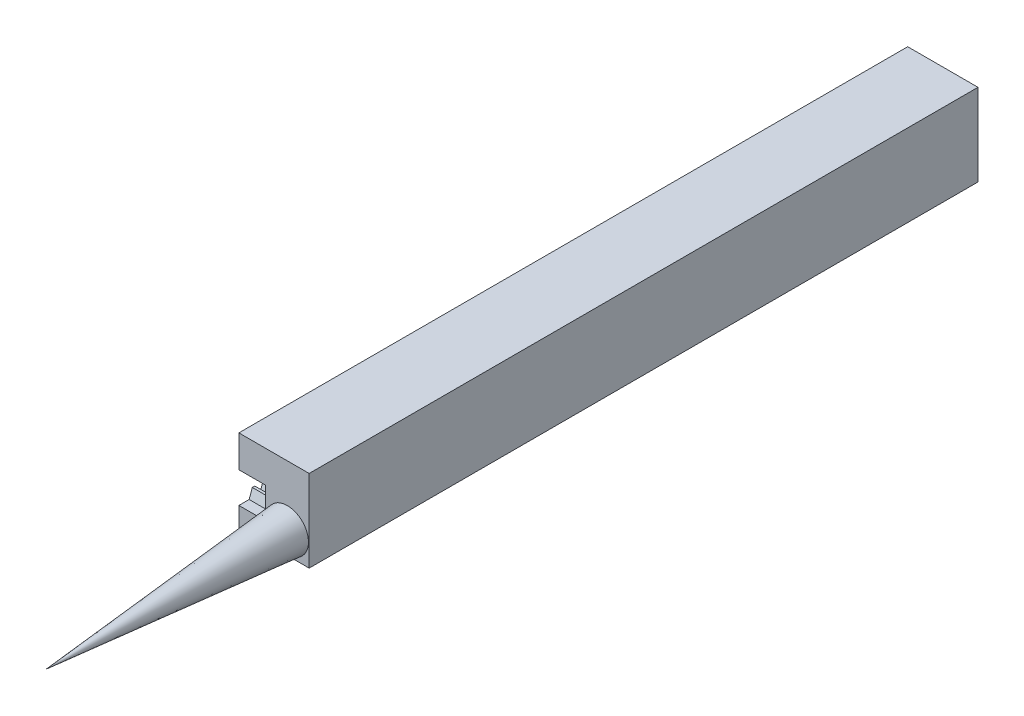
SolidWorks part; units mm, degrees
ref_plane "Ebene vorne" through (0, 0, 0) normal (0, 0, 1) x (1, 0, 0)
ref_plane "Ebene oben" through (0, 0, 0) normal (0, 1, 0) x (1, 0, 0)
ref_plane "Ebene rechts" through (0, 0, 0) normal (1, 0, 0) x (0, 0, -1)
sketch "Skizze1" plane through (0, 0, 0) normal (0, 0, 1) x (1, 0, 0)
  line L1 (-33, -38.5) -> (33, -38.5)
  line L2 (-33, -38.5) -> (-33, 38.5)
  line L3 (-33, 38.5) -> (33, 38.5)
  line L4 (33, -38.5) -> (33, 38.5)
  line L5 (-33, -38.5) -> (33, 38.5) construction
  line L6 (-33, 38.5) -> (33, -38.5) construction
  point P0 (0, 0)
  dimension "D1" = 77
  dimension "D2" = 66
extrude "Aufsatz-Linear austragen1" add sketch "Skizze1" along normal blind 628
sketch "Skizze2" plane through (0, 0, 0) normal (0, 0, -1) x (-1, 0, 0)
  line L0 (33, -20.5) -> (33, 8.5)
  line L1 (33, -20.5) -> (8, -20.5)
  line L2 (33, 8.5) -> (8, 8.5)
  line L3 (8, -20.5) -> (8, 8.5)
  line L4 (33, 38.5) -> (33, -38.5) construction
  line L5 (33, -38.5) -> (-33, -38.5) construction
  dimension "D1" = 18
  dimension "D2" = 25
  dimension "D3" = 29
extrude "Schnitt-Linear austragen1" cut sketch "Skizze2" against normal up to surface (628 mm away) up to face at (0, 0, 628)
sketch "Skizze3" plane through (-8, 0, 0) normal (-1, 0, 0) x (0, 0, 1)
  line L0 (18.367, -20.5) -> (10, -20.5)
  line L1 (0, -20.5) -> (3.0059, -12.2151)
  line L2 (3.0059, -12.2151) -> (5.361, -12.2151)
  line L3 (5.361, -12.2151) -> (8.367, -20.5)
  line L4 (628, -20.5) -> (0, -20.5) construction
  line L5 (8.367, -20.5) -> (0, -20.5)
  line L6 (10, -20.5) -> (13.0059, -12.2151)
  line L7 (13.0059, -12.2151) -> (15.361, -12.2151)
  line L8 (15.361, -12.2151) -> (18.367, -20.5)
  line L9 (28.367, -20.5) -> (20, -20.5)
  line L10 (20, -20.5) -> (23.0059, -12.2151)
  line L11 (23.0059, -12.2151) -> (25.361, -12.2151)
  line L12 (25.361, -12.2151) -> (28.367, -20.5)
  line L13 (38.367, -20.5) -> (30, -20.5)
  line L14 (30, -20.5) -> (33.0059, -12.2151)
  line L15 (33.0059, -12.2151) -> (35.361, -12.2151)
  line L16 (35.361, -12.2151) -> (38.367, -20.5)
  line L17 (48.367, -20.5) -> (40, -20.5)
  line L18 (40, -20.5) -> (43.0059, -12.2151)
  line L19 (43.0059, -12.2151) -> (45.361, -12.2151)
  line L20 (45.361, -12.2151) -> (48.367, -20.5)
  line L21 (58.367, -20.5) -> (50, -20.5)
  line L22 (50, -20.5) -> (53.0059, -12.2151)
  line L23 (53.0059, -12.2151) -> (55.361, -12.2151)
  line L24 (55.361, -12.2151) -> (58.367, -20.5)
  line L25 (68.367, -20.5) -> (60, -20.5)
  line L26 (60, -20.5) -> (63.0059, -12.2151)
  line L27 (63.0059, -12.2151) -> (65.361, -12.2151)
  line L28 (65.361, -12.2151) -> (68.367, -20.5)
  line L29 (78.367, -20.5) -> (70, -20.5)
  line L30 (70, -20.5) -> (73.0059, -12.2151)
  line L31 (73.0059, -12.2151) -> (75.361, -12.2151)
  line L32 (75.361, -12.2151) -> (78.367, -20.5)
  line L33 (88.367, -20.5) -> (80, -20.5)
  line L34 (80, -20.5) -> (83.0059, -12.2151)
  line L35 (83.0059, -12.2151) -> (85.361, -12.2151)
  line L36 (85.361, -12.2151) -> (88.367, -20.5)
  line L37 (98.367, -20.5) -> (90, -20.5)
  line L38 (90, -20.5) -> (93.0059, -12.2151)
  line L39 (93.0059, -12.2151) -> (95.361, -12.2151)
  line L40 (95.361, -12.2151) -> (98.367, -20.5)
  line L41 (108.367, -20.5) -> (100, -20.5)
  line L42 (100, -20.5) -> (103.0059, -12.2151)
  line L43 (103.0059, -12.2151) -> (105.361, -12.2151)
  line L44 (105.361, -12.2151) -> (108.367, -20.5)
  line L45 (118.367, -20.5) -> (110, -20.5)
  line L46 (110, -20.5) -> (113.0059, -12.2151)
  line L47 (113.0059, -12.2151) -> (115.361, -12.2151)
  line L48 (115.361, -12.2151) -> (118.367, -20.5)
  line L49 (128.367, -20.5) -> (120, -20.5)
  line L50 (120, -20.5) -> (123.0059, -12.2151)
  line L51 (123.0059, -12.2151) -> (125.361, -12.2151)
  line L52 (125.361, -12.2151) -> (128.367, -20.5)
  line L53 (138.367, -20.5) -> (130, -20.5)
  line L54 (130, -20.5) -> (133.0059, -12.2151)
  line L55 (133.0059, -12.2151) -> (135.361, -12.2151)
  line L56 (135.361, -12.2151) -> (138.367, -20.5)
  line L57 (148.367, -20.5) -> (140, -20.5)
  line L58 (140, -20.5) -> (143.0059, -12.2151)
  line L59 (143.0059, -12.2151) -> (145.361, -12.2151)
  line L60 (145.361, -12.2151) -> (148.367, -20.5)
  line L61 (158.367, -20.5) -> (150, -20.5)
  line L62 (150, -20.5) -> (153.0059, -12.2151)
  line L63 (153.0059, -12.2151) -> (155.361, -12.2151)
  line L64 (155.361, -12.2151) -> (158.367, -20.5)
  line L65 (168.367, -20.5) -> (160, -20.5)
  line L66 (160, -20.5) -> (163.0059, -12.2151)
  line L67 (163.0059, -12.2151) -> (165.361, -12.2151)
  line L68 (165.361, -12.2151) -> (168.367, -20.5)
  line L69 (178.367, -20.5) -> (170, -20.5)
  line L70 (170, -20.5) -> (173.0059, -12.2151)
  line L71 (173.0059, -12.2151) -> (175.361, -12.2151)
  line L72 (175.361, -12.2151) -> (178.367, -20.5)
  line L73 (188.367, -20.5) -> (180, -20.5)
  line L74 (180, -20.5) -> (183.0059, -12.2151)
  line L75 (183.0059, -12.2151) -> (185.361, -12.2151)
  line L76 (185.361, -12.2151) -> (188.367, -20.5)
  line L77 (198.367, -20.5) -> (190, -20.5)
  line L78 (190, -20.5) -> (193.0059, -12.2151)
  line L79 (193.0059, -12.2151) -> (195.361, -12.2151)
  line L80 (195.361, -12.2151) -> (198.367, -20.5)
  line L81 (208.367, -20.5) -> (200, -20.5)
  line L82 (200, -20.5) -> (203.0059, -12.2151)
  line L83 (203.0059, -12.2151) -> (205.361, -12.2151)
  line L84 (205.361, -12.2151) -> (208.367, -20.5)
  line L85 (218.367, -20.5) -> (210, -20.5)
  line L86 (210, -20.5) -> (213.0059, -12.2151)
  line L87 (213.0059, -12.2151) -> (215.361, -12.2151)
  line L88 (215.361, -12.2151) -> (218.367, -20.5)
  line L89 (228.367, -20.5) -> (220, -20.5)
  line L90 (220, -20.5) -> (223.0059, -12.2151)
  line L91 (223.0059, -12.2151) -> (225.361, -12.2151)
  line L92 (225.361, -12.2151) -> (228.367, -20.5)
  line L93 (238.367, -20.5) -> (230, -20.5)
  line L94 (230, -20.5) -> (233.0059, -12.2151)
  line L95 (233.0059, -12.2151) -> (235.361, -12.2151)
  line L96 (235.361, -12.2151) -> (238.367, -20.5)
  line L97 (248.367, -20.5) -> (240, -20.5)
  line L98 (240, -20.5) -> (243.0059, -12.2151)
  line L99 (243.0059, -12.2151) -> (245.361, -12.2151)
  line L100 (245.361, -12.2151) -> (248.367, -20.5)
  line L101 (258.367, -20.5) -> (250, -20.5)
  line L102 (250, -20.5) -> (253.0059, -12.2151)
  line L103 (253.0059, -12.2151) -> (255.361, -12.2151)
  line L104 (255.361, -12.2151) -> (258.367, -20.5)
  line L105 (268.367, -20.5) -> (260, -20.5)
  line L106 (260, -20.5) -> (263.0059, -12.2151)
  line L107 (263.0059, -12.2151) -> (265.361, -12.2151)
  line L108 (265.361, -12.2151) -> (268.367, -20.5)
  line L109 (278.367, -20.5) -> (270, -20.5)
  line L110 (270, -20.5) -> (273.0059, -12.2151)
  line L111 (273.0059, -12.2151) -> (275.361, -12.2151)
  line L112 (275.361, -12.2151) -> (278.367, -20.5)
  line L113 (288.367, -20.5) -> (280, -20.5)
  line L114 (280, -20.5) -> (283.0059, -12.2151)
  line L115 (283.0059, -12.2151) -> (285.361, -12.2151)
  line L116 (285.361, -12.2151) -> (288.367, -20.5)
  line L117 (298.367, -20.5) -> (290, -20.5)
  line L118 (290, -20.5) -> (293.0059, -12.2151)
  line L119 (293.0059, -12.2151) -> (295.361, -12.2151)
  line L120 (295.361, -12.2151) -> (298.367, -20.5)
  line L121 (308.367, -20.5) -> (300, -20.5)
  line L122 (300, -20.5) -> (303.0059, -12.2151)
  line L123 (303.0059, -12.2151) -> (305.361, -12.2151)
  line L124 (305.361, -12.2151) -> (308.367, -20.5)
  line L125 (318.367, -20.5) -> (310, -20.5)
  line L126 (310, -20.5) -> (313.0059, -12.2151)
  line L127 (313.0059, -12.2151) -> (315.361, -12.2151)
  line L128 (315.361, -12.2151) -> (318.367, -20.5)
  line L129 (328.367, -20.5) -> (320, -20.5)
  line L130 (320, -20.5) -> (323.0059, -12.2151)
  line L131 (323.0059, -12.2151) -> (325.361, -12.2151)
  line L132 (325.361, -12.2151) -> (328.367, -20.5)
  line L133 (338.367, -20.5) -> (330, -20.5)
  line L134 (330, -20.5) -> (333.0059, -12.2151)
  line L135 (333.0059, -12.2151) -> (335.361, -12.2151)
  line L136 (335.361, -12.2151) -> (338.367, -20.5)
  line L137 (348.367, -20.5) -> (340, -20.5)
  line L138 (340, -20.5) -> (343.0059, -12.2151)
  line L139 (343.0059, -12.2151) -> (345.361, -12.2151)
  line L140 (345.361, -12.2151) -> (348.367, -20.5)
  line L141 (358.367, -20.5) -> (350, -20.5)
  line L142 (350, -20.5) -> (353.0059, -12.2151)
  line L143 (353.0059, -12.2151) -> (355.361, -12.2151)
  line L144 (355.361, -12.2151) -> (358.367, -20.5)
  line L145 (368.367, -20.5) -> (360, -20.5)
  line L146 (360, -20.5) -> (363.0059, -12.2151)
  line L147 (363.0059, -12.2151) -> (365.361, -12.2151)
  line L148 (365.361, -12.2151) -> (368.367, -20.5)
  line L149 (378.367, -20.5) -> (370, -20.5)
  line L150 (370, -20.5) -> (373.0059, -12.2151)
  line L151 (373.0059, -12.2151) -> (375.361, -12.2151)
  line L152 (375.361, -12.2151) -> (378.367, -20.5)
  line L153 (388.367, -20.5) -> (380, -20.5)
  line L154 (380, -20.5) -> (383.0059, -12.2151)
  line L155 (383.0059, -12.2151) -> (385.361, -12.2151)
  line L156 (385.361, -12.2151) -> (388.367, -20.5)
  line L157 (398.367, -20.5) -> (390, -20.5)
  line L158 (390, -20.5) -> (393.0059, -12.2151)
  line L159 (393.0059, -12.2151) -> (395.361, -12.2151)
  line L160 (395.361, -12.2151) -> (398.367, -20.5)
  line L161 (408.367, -20.5) -> (400, -20.5)
  line L162 (400, -20.5) -> (403.0059, -12.2151)
  line L163 (403.0059, -12.2151) -> (405.361, -12.2151)
  line L164 (405.361, -12.2151) -> (408.367, -20.5)
  line L165 (418.367, -20.5) -> (410, -20.5)
  line L166 (410, -20.5) -> (413.0059, -12.2151)
  line L167 (413.0059, -12.2151) -> (415.361, -12.2151)
  line L168 (415.361, -12.2151) -> (418.367, -20.5)
  line L169 (428.367, -20.5) -> (420, -20.5)
  line L170 (420, -20.5) -> (423.0059, -12.2151)
  line L171 (423.0059, -12.2151) -> (425.361, -12.2151)
  line L172 (425.361, -12.2151) -> (428.367, -20.5)
  line L173 (438.367, -20.5) -> (430, -20.5)
  line L174 (430, -20.5) -> (433.0059, -12.2151)
  line L175 (433.0059, -12.2151) -> (435.361, -12.2151)
  line L176 (435.361, -12.2151) -> (438.367, -20.5)
  line L177 (448.367, -20.5) -> (440, -20.5)
  line L178 (440, -20.5) -> (443.0059, -12.2151)
  line L179 (443.0059, -12.2151) -> (445.361, -12.2151)
  line L180 (445.361, -12.2151) -> (448.367, -20.5)
  line L181 (458.367, -20.5) -> (450, -20.5)
  line L182 (450, -20.5) -> (453.0059, -12.2151)
  line L183 (453.0059, -12.2151) -> (455.361, -12.2151)
  line L184 (455.361, -12.2151) -> (458.367, -20.5)
  line L185 (468.367, -20.5) -> (460, -20.5)
  line L186 (460, -20.5) -> (463.0059, -12.2151)
  line L187 (463.0059, -12.2151) -> (465.361, -12.2151)
  line L188 (465.361, -12.2151) -> (468.367, -20.5)
  line L189 (478.367, -20.5) -> (470, -20.5)
  line L190 (470, -20.5) -> (473.0059, -12.2151)
  line L191 (473.0059, -12.2151) -> (475.361, -12.2151)
  line L192 (475.361, -12.2151) -> (478.367, -20.5)
  line L193 (488.367, -20.5) -> (480, -20.5)
  line L194 (480, -20.5) -> (483.0059, -12.2151)
  line L195 (483.0059, -12.2151) -> (485.361, -12.2151)
  line L196 (485.361, -12.2151) -> (488.367, -20.5)
  line L197 (498.367, -20.5) -> (490, -20.5)
  line L198 (490, -20.5) -> (493.0059, -12.2151)
  line L199 (493.0059, -12.2151) -> (495.361, -12.2151)
  line L200 (495.361, -12.2151) -> (498.367, -20.5)
  line L201 (508.367, -20.5) -> (500, -20.5)
  line L202 (500, -20.5) -> (503.0059, -12.2151)
  line L203 (503.0059, -12.2151) -> (505.361, -12.2151)
  line L204 (505.361, -12.2151) -> (508.367, -20.5)
  line L205 (518.367, -20.5) -> (510, -20.5)
  line L206 (510, -20.5) -> (513.0059, -12.2151)
  line L207 (513.0059, -12.2151) -> (515.361, -12.2151)
  line L208 (515.361, -12.2151) -> (518.367, -20.5)
  line L209 (528.367, -20.5) -> (520, -20.5)
  line L210 (520, -20.5) -> (523.0059, -12.2151)
  line L211 (523.0059, -12.2151) -> (525.361, -12.2151)
  line L212 (525.361, -12.2151) -> (528.367, -20.5)
  line L213 (538.367, -20.5) -> (530, -20.5)
  line L214 (530, -20.5) -> (533.0059, -12.2151)
  line L215 (533.0059, -12.2151) -> (535.361, -12.2151)
  line L216 (535.361, -12.2151) -> (538.367, -20.5)
  line L217 (548.367, -20.5) -> (540, -20.5)
  line L218 (540, -20.5) -> (543.0059, -12.2151)
  line L219 (543.0059, -12.2151) -> (545.361, -12.2151)
  line L220 (545.361, -12.2151) -> (548.367, -20.5)
  line L221 (558.367, -20.5) -> (550, -20.5)
  line L222 (550, -20.5) -> (553.0059, -12.2151)
  line L223 (553.0059, -12.2151) -> (555.361, -12.2151)
  line L224 (555.361, -12.2151) -> (558.367, -20.5)
  line L225 (568.367, -20.5) -> (560, -20.5)
  line L226 (560, -20.5) -> (563.0059, -12.2151)
  line L227 (563.0059, -12.2151) -> (565.361, -12.2151)
  line L228 (565.361, -12.2151) -> (568.367, -20.5)
  line L229 (578.367, -20.5) -> (570, -20.5)
  line L230 (570, -20.5) -> (573.0059, -12.2151)
  line L231 (573.0059, -12.2151) -> (575.361, -12.2151)
  line L232 (575.361, -12.2151) -> (578.367, -20.5)
  line L233 (588.367, -20.5) -> (580, -20.5)
  line L234 (580, -20.5) -> (583.0059, -12.2151)
  line L235 (583.0059, -12.2151) -> (585.361, -12.2151)
  line L236 (585.361, -12.2151) -> (588.367, -20.5)
  line L237 (598.367, -20.5) -> (590, -20.5)
  line L238 (590, -20.5) -> (593.0059, -12.2151)
  line L239 (593.0059, -12.2151) -> (595.361, -12.2151)
  line L240 (595.361, -12.2151) -> (598.367, -20.5)
  line L241 (608.367, -20.5) -> (600, -20.5)
  line L242 (600, -20.5) -> (603.0059, -12.2151)
  line L243 (603.0059, -12.2151) -> (605.361, -12.2151)
  line L244 (605.361, -12.2151) -> (608.367, -20.5)
  line L245 (618.367, -20.5) -> (610, -20.5)
  line L246 (610, -20.5) -> (613.0059, -12.2151)
  line L247 (613.0059, -12.2151) -> (615.361, -12.2151)
  line L248 (615.361, -12.2151) -> (618.367, -20.5)
  line L249 (8.367, -20.5) -> (18.367, -20.5) construction
  dimension "D1" = 10
  dimension "D2" = 62
extrude "Aufsatz-Linear austragen3" add sketch "Skizze3" along normal up to vertex (25 mm away)
sketch "Skizze4" plane through (0, 0, 628) normal (0, 0, 1) x (1, 0, 0)
  circle A0 centre (12.5183, -17.6909) radius 19.8251
  point P2 (0, 0)
  point P3 (12.5183, -17.6909)
extrude "Aufsatz-Linear austragen4" add sketch "Skizze4" along normal blind 228 draft 5
